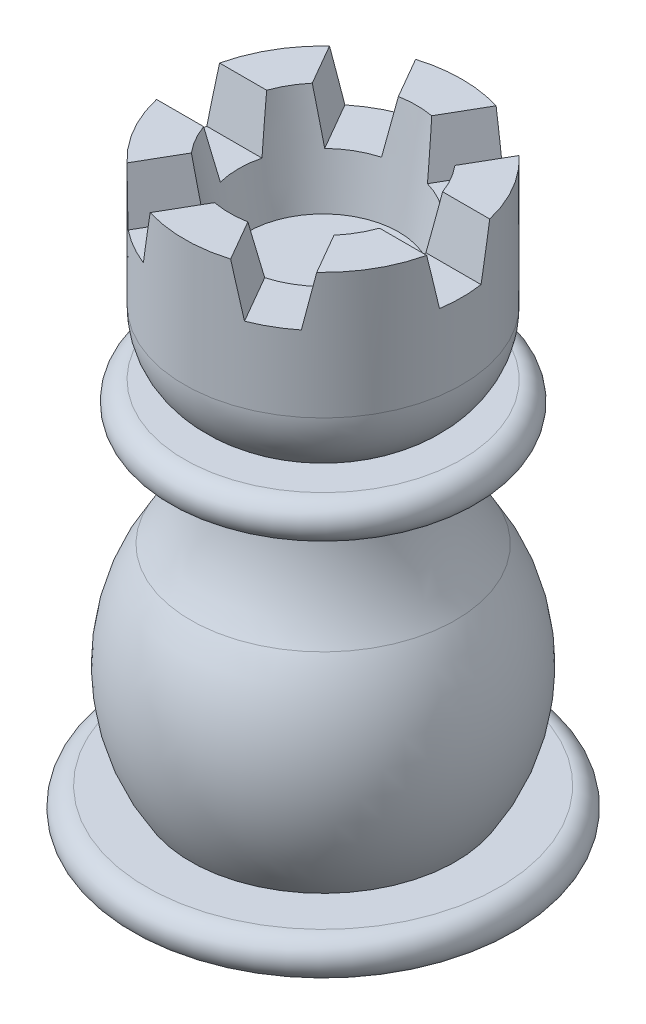
SolidWorks part; units mm, degrees
material "ABS"
ref_plane "Front Plane" through (0, 0, 0) normal (0, 0, 1) x (1, 0, 0)
ref_plane "Top Plane" through (0, 0, 0) normal (0, 1, 0) x (1, 0, 0)
ref_plane "Right Plane" through (0, 0, 0) normal (1, 0, 0) x (0, 0, -1)
sketch "Sketch1" plane through (0, 0, 0) normal (1, 0, 0) x (0, 0, -1)
  line L0 (0, 0) -> (-14, 0)
  line L1 (-14, 3) -> (-10.5, 3)
  line L2 (0, 0) -> (0, 38) construction
  line L3 (0, 38) -> (-6, 38)
  line L4 (-6, 38) -> (-7.4106, 46)
  line L5 (-7.4106, 46) -> (-11, 46)
  line L6 (-11, 46) -> (-11, 36)
  line L7 (-8.1195, 30.8747) -> (-11, 30.8747)
  line L8 (-11, 27.8747) -> (-8, 27.8747)
  line L9 (-13, 11.2916) -> (-13, 3) construction
  line L10 (0, 0) -> (0, 38) construction
  line L12 (0, 38) -> (0, 0)
  arc A0 (-14, 0) -> (-14, 3) centre (-14, 1.5) cw
  arc A1 (-11, 36) -> (-8.1195, 30.8747) centre (-5, 36) ccw
  arc A2 (-11, 30.8747) -> (-11, 27.8747) centre (-11, 29.3747) ccw
  arc A3 (-8, 27.8747) -> (-10.5, 19.5831) centre (-23, 27.8747) cw
  arc A4 (-10.5, 19.5831) -> (-10.5, 3) centre (2, 11.2916) ccw
  dimension "D2" = 1.5
  dimension "D3" = 6
  dimension "D12" = 15
  dimension "D1" = 46
  dimension "D4" = 80
  dimension "D5" = 11
  dimension "D6" = 8
  dimension "D7" = 6
  dimension "D8" = 2
  dimension "D10" = 22
  dimension "D11" = 16
  dimension "D13" = 26
  dimension "D14" = 28
revolve "Revolve1" add sketch "Sketch1" angle 360 about L10
sketch "Sketch2" plane through (0, 0, 0) normal (1, 0, 0) x (0, 0, -1)
  line L0 (0, 46) -> (0, 42) construction
  line L1 (11, 46) -> (-11, 46) construction
  line L2 (1.6498, 42) -> (-1.6498, 42)
  line L3 (-1.6498, 42) -> (-2.5, 46)
  line L4 (-2.5, 46) -> (2.5, 46)
  line L5 (1.6498, 42) -> (2.5, 46)
  dimension "D1" = 4
  dimension "D2" = 5
  dimension "D3" = 12
extrude "Cut-Extrude1" cut sketch "Sketch2" against normal through all both and the other way through all
pattern_circular "CirPattern1" count 3 over 360 about axis through (0, 0, 0) along (0, 1, 0) of "Cut-Extrude1"
